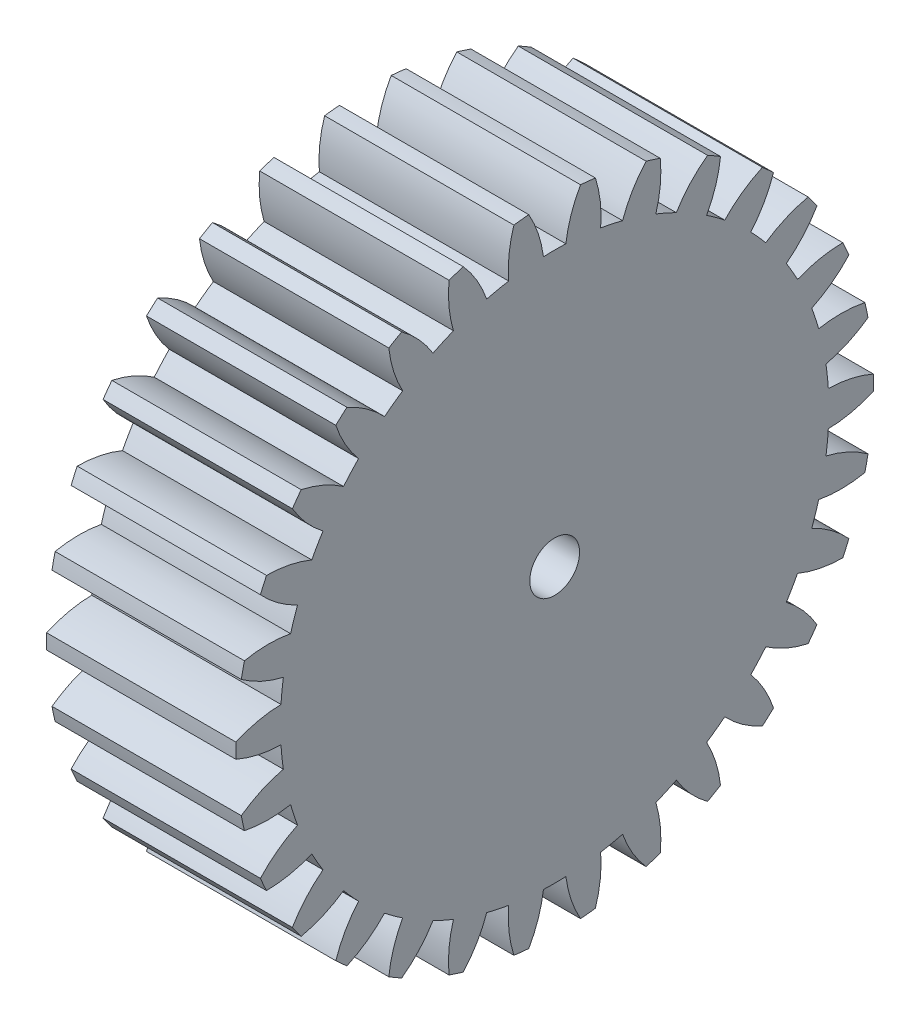
SolidWorks part; units mm, degrees
ref_plane "Plane1" through (0, 0, 0) normal (0, 0, 1) x (1, 0, 0)
ref_plane "Plane2" through (0, 0, 0) normal (0, 1, 0) x (1, 0, 0)
ref_plane "Plane3" through (0, 0, 0) normal (1, 0, 0) x (0, 0, -1)
sketch "HoldingSke" plane through (0, 0, 0) normal (0, 1, 0) x (1, 0, 0)
  line L0 (0, 0) -> (439.9409, -254)
  line L1 (-15, 0) -> (100, 0) construction
  line L2 (0, 0) -> (-2.1039, 2.3779)
  line L3 (0, 0) -> (-11.863, 4.5341)
  line L4 (0, 0) -> (7.479, 4.318)
  line L5 (0, 0) -> (-47.5972, -17.7524)
  line L6 (0, 0) -> (-10.0014, -6.748)
  line L7 (-2.1039, 2.3779) -> (8.8308, 51.9871)
  line L8 (-76.2, 54.61) -> (-72.771, 54.61)
  line L9 (-67.7845, 28.3722) -> (-49.3413, 33.142)
  line L10 (-76.2, 71.12) -> (104.1128, 71.12)
  line L11 (0, 0) -> (-12.065, 0)
  line L12 (-76.2, 101.6) -> (-76.1492, 101.6)
  line L13 (24.9733, 27.94) -> (52.9518, 28.4284)
  line L14 (24.9733, 27.94) -> (25.0241, 27.9398)
  line L15 (24.9733, 27.94) -> (100.4021, 29.52)
  circle A0 centre (0, 0) radius 1.5875
  circle A1 centre (0, 0) radius 17.4752
  circle A2 centre (0, 0) radius 38.1
  circle A3 centre (0, 0) radius 1.5875
  dimension "MHD" = 34.9504
  dimension "Hub_dia" = 76.2
  dimension "Bore" = 3.175
  dimension "MBD" = 3.175
  dimension "Num_teeth" = 30
  dimension "Pitch" = 508
  dimension "Overall_len" = 50.8
  dimension "Show_teeth" = 30
  dimension "Thickness" = 12.065
  dimension "OAL" = 50.8001
  dimension "T_dim" = 3.429
  dimension "Ap" = 14.5
  dimension "H" = 19.05
  dimension "Pitch_radius" = 180.3128
  dimension "Width" = 12.065
  dimension "Backlash" = 0.0508
  dimension "Addendum_fac" = 1
  dimension "Dedendum_fac" = 1.2
  dimension "Clearance_fac" = 0.2
  dimension "Dedendum_add" = 0.0508
sketch "BasProSke" plane through (0, 0, 0) normal (0, 1, 0) x (1, 0, 0)
  line L0 (-10, 0) -> (60, 0) construction
  line L1 (0, 0) -> (0, 20.32)
  line L2 (0, 0) -> (12.065, 0)
  line L3 (12.065, 0) -> (12.065, 20.32)
  line L4 (12.065, 20.32) -> (0, 20.32)
  dimension "Thickness" = 12.065
  dimension "Diameter" = 40.64
revolve "Base-Revolve" add sketch "BasProSke" angle 360 about L0
sketch "TooCutSke" plane through (0, 0, 0) normal (1, 0, 0) x (0, 0, -1)
  line L1 (0, 0) -> (0, 107) construction
  line L2 (0, 0) -> (-1.0859, 19.019) construction
  line L3 (0, 0) -> (-3.978, 37.8482) construction
  line L4 (-1.0859, 19.019) -> (-1.989, 18.9241) construction
  arc A0 (0.7147, 17.4606) -> (-0.7147, 17.4606) centre (0, 0) ccw
  arc A1 (1.6631, 20.2773) -> (-1.6631, 20.2773) centre (0, 0) ccw
  circle A2 centre (0, 0) radius 19.05 construction
  circle A3 centre (0, 0) radius 18.4432 construction
  arc A4 (-0.7147, 17.4606) -> (-1.6631, 20.2773) centre (-8.2719, 16.4842) ccw
  arc A5 (1.6631, 20.2773) -> (0.7147, 17.4606) centre (8.2719, 16.4842) ccw
  dimension "Root_dia" = 34.9504
  dimension "Overcut_dia" = 40.6908
  dimension "Pitch_dia" = 38.1
  dimension "Base_dia" = 36.8864
  dimension "Flank_rad" = 7.62
  dimension "Half_ang" = 6
  dimension "Half_CT" = 0.9081
extrude "ToothCut" cut sketch "TooCutSke" along normal through all
fillet "Breaks" [suppressed] radius 0.0254
fillet "RootFillets" [suppressed] radius 0.3048
pattern_circular "TeethCuts" count 30 every 12 about axis through (-10, 0, 0) along (1, 0, 0) of "ToothCut", "RootFillets", "Breaks"
sketch "HubNeaOneSke" plane through (0, 0, 0) normal (-1, 0, 0) x (0, 0, 1)
  circle A0 centre (0, 0) radius 17.4752
  dimension "Diameter" = 34.9504
extrude "HubNearOne" [suppressed] add sketch "HubNeaOneSke" along normal blind 38.7351
sketch "HubNeaBotSke" plane through (0, 0, 0) normal (-1, 0, 0) x (0, 0, 1)
  circle A0 centre (0, 0) radius 17.4752
  dimension "Diameter" = 34.9504
extrude "HubNearBoth" [suppressed] add sketch "HubNeaBotSke" along normal blind 19.3675
ref_plane "FarPln" through (12.065, 0, 0) normal (1, 0, 0) x (0, 0, -1)
sketch "HubFarSke" plane through (12.065, 0, 0) normal (1, 0, 0) x (0, 0, -1)
  circle A0 centre (0, 0) radius 17.4752
  dimension "Diameter" = 34.9504
extrude "HubFar" [suppressed] add sketch "HubFarSke" along normal blind 19.3675
sketch "BorSke" plane through (0, 0, 0) normal (1, 0, 0) x (0, 0, -1)
  circle A0 centre (0, 0) radius 1.5875
  dimension "Diameter" = 3.175
extrude "Bore" cut sketch "BorSke" along normal mid plane 101.6001
sketch "KeySke" plane through (0, 0, 0) normal (1, 0, 0) x (0, 0, -1)
  line L0 (-0.127, 0) -> (-0.127, 1.8415)
  line L1 (-0.127, 1.8415) -> (0.127, 1.8415)
  line L2 (0.127, 1.8415) -> (0.127, 0)
  line L3 (0, 0) -> (0, 34) construction
  line L4 (-0.127, 0) -> (0.127, 0)
  dimension "Offset" = 1.8415
  dimension "Width" = 0.254
extrude "Keyway" [suppressed] cut sketch "KeySke" along normal mid plane 101.6001
pattern_circular "Keyway2" [suppressed] count 2 every 90 about axis through (-10, 0, 0) along (1, 0, 0)
equation "' \"Pitch@HoldingSke\" = 4"
equation "' \"Num_teeth@HoldingSke\" = 12"
equation "' \"Ap@HoldingSke\" =  20"
equation "' \"Ap@HoldingSke\" = 20"
equation "' \"Width@HoldingSke\" = 0.5"
equation "' \"Hub_dia@HoldingSke\"= 1"
equation "' \"Hub_dia@HoldingSke\" = 1"
equation "' \"Overall_len@HoldingSke\" = 1.0"
equation "' \"Bore@HoldingSke\" = 0.75"
equation "' \"T_dim@HoldingSke\" = 0.85"
equation "' \"Width@KeySke\" = 0.25"
equation "' \"Show_teeth@HoldingSke\" = 13"
equation "' \"Backlash@HoldingSke\" = 0.009"
equation "' \"Addendum_fac@HoldingSke\" = 1.0"
equation "' \"Dedendum_fac@HoldingSke\" = 1.25"
equation "' \"Dedendum_add@HoldingSke\" = 0.00005"
equation "' \"Clearance_fac@HoldingSke\" = 0.25"
equation "' \"Pitch@HoldingSke\" = 0.5"
equation "' \"Num_teeth@HoldingSke\" = 23"
equation "' \"Show_teeth@HoldingSke\" = 23"
equation "' \"Backlash@HoldingSke\" = 0.0375"
equation "\"Overcut_dia@TooCutSke\" = (\"Num_teeth@HoldingSke\" + 2 * \"Addendum_fac@HoldingSke\") / \"Pitch@HoldingSke\" + 0.002"
equation "\"Pitch_dia@TooCutSke\" = \"Num_teeth@HoldingSke\" / \"Pitch@HoldingSke\""
equation "\"Base_dia@TooCutSke\" = \"Num_teeth@HoldingSke\" / \"Pitch@HoldingSke\" * cos((\"Ap@HoldingSke\"  * 3.14159265 / 180))"
equation "\"Root_dia@TooCutSke\" = (\"Num_teeth@HoldingSke\" + 2) / \"Pitch@HoldingSke\" - 2 * (\"Addendum_fac@HoldingSke\" + \"Dedendum_fac@HoldingSke\") / \"Pitch@HoldingSke\" - \"Dedendum_add@HoldingSke\" * 2"
equation "\"Half_ang@TooCutSke\" = 180 / \"Num_teeth@HoldingSke\""
equation "\"Half_CT@TooCutSke\" = \"Num_teeth@HoldingSke\" / \"Pitch@HoldingSke\" * sin((3.14159265 / 2 / \"Num_teeth@HoldingSke\")) / 2 - 7 * \"Backlash@HoldingSke\" / 4"
equation "\"Flank_rad@TooCutSke\" = \"Num_teeth@HoldingSke\" / \"Pitch@HoldingSke\" / 5"
equation "\"Radius@RootFillets\" = \"Clearance_fac@HoldingSke\" / \"Pitch@HoldingSke\" + \"Dedendum_add@HoldingSke\""
equation "\"Break_rad@Breaks\" = 0.02 / \"Pitch@HoldingSke\""
equation "\"Thickness@HoldingSke\" = \"Width@HoldingSke\""
equation "\"OAL@HoldingSke\" = \"Thickness@HoldingSke\""
equation "\"MHD@HoldingSke\" = (\"Num_teeth@HoldingSke\" + 2) / \"Pitch@HoldingSke\" - 2 * (\"Addendum_fac@HoldingSke\" + \"Dedendum_fac@HoldingSke\")  / \"Pitch@HoldingSke\" - \"Dedendum_add@HoldingSke\" * 2"
equation "\"MBD@HoldingSke\" = (\"Num_teeth@HoldingSke\" + 2) / \"Pitch@HoldingSke\" - 2 * (\"Addendum_fac@HoldingSke\" + \"Dedendum_fac@HoldingSke\")  / \"Pitch@HoldingSke\" - \"Dedendum_add@HoldingSke\" * 2 - 0.002"
equation "\"MHD@HoldingSke\" = ((sgn( \"MHD@HoldingSke\" - \"Hub_dia@HoldingSke\" )-1)*( \"MHD@HoldingSke\" - \"Hub_dia@HoldingSke\" ))/-2+ \"Hub_dia@HoldingSke\""
equation "\"MBD@HoldingSke\" = ((sgn( \"MBD@HoldingSke\" - \"Bore@HoldingSke\" )-1)*( \"MBD@HoldingSke\" - \"Bore@HoldingSke\" ))/-2+ \"Bore@HoldingSke\""
equation "\"OAL@HoldingSke\" = ((sgn( \"OAL@HoldingSke\" - \"Overall_len@HoldingSke\" )+1)*( \"OAL@HoldingSke\" - \"Overall_len@HoldingSke\" ))/2 + \"Overall_len@HoldingSke\" + 0.000002"
equation "\"Num_teeth@TeethCuts\" = int( \"Show_teeth@HoldingSke\" ) + 1"
equation "\"Num_teeth@TeethCuts\" = ((sgn( \"Num_teeth@TeethCuts\" - \"Num_teeth@HoldingSke\" )-1)*( \"Num_teeth@TeethCuts\" - \"Num_teeth@HoldingSke\" ))/-2+ \"Num_teeth@HoldingSke\""
equation "\"Num_teeth@TeethCuts\" = ((sgn( \"Num_teeth@TeethCuts\" - 2.0)+1)*( \"Num_teeth@TeethCuts\" - 2.0))/2 +2.0"
equation "\"Angle@TeethCuts\" = 360.0 / \"Num_teeth@HoldingSke\""
equation "\"Diameter@BasProSke\" = (\"Num_teeth@HoldingSke\" + 2 * \"Addendum_fac@HoldingSke\") / \"Pitch@HoldingSke\""
equation "\"Thickness@BasProSke\"  = \"Thickness@HoldingSke\""
equation "' \"Fillet_rad@BasProSke\" =  \"Thickness@HoldingSke\" * 0.05"
equation "' \"Fillet_rad@BasProSke\" = \"Thickness@HoldingSke\" * 0.05"
equation "\"MHD@HoldingSke\" = ((sgn( \"MHD@HoldingSke\" - \"Root_dia@TooCutSke\" )-1)*( \"MHD@HoldingSke\" - \"Root_dia@TooCutSke\" ))/-2+ \"Root_dia@TooCutSke\""
equation "\"Diameter@HubNeaOneSke\" = \"MHD@HoldingSke\""
equation "\"Length@HubNearOne\" = \"OAL@HoldingSke\" - \"Thickness@BasProSke\""
equation "\"Diameter@HubNeaBotSke\" = \"MHD@HoldingSke\""
equation "\"Length@HubNearBoth\" = ( \"OAL@HoldingSke\" - \"Thickness@BasProSke\" ) / 2.0"
equation "\"Thickness@FarPln\" = \"Thickness@BasProSke\""
equation "\"Diameter@HubFarSke\" = \"MHD@HoldingSke\""
equation "\"Length@HubFar\" = ( \"OAL@HoldingSke\" - \"Thickness@BasProSke\" ) / 2.0"
equation "\"Diameter@BorSke\" = \"MBD@HoldingSke\""
equation "\"D1@Bore\" = \"OAL@HoldingSke\" * 2.0"
equation "\"D1@Keyway\" = \"OAL@HoldingSke\" * 2.0"
equation "\"Offset@KeySke\" = \"T_dim@HoldingSke\" - \"MBD@HoldingSke\" / 2.0"
